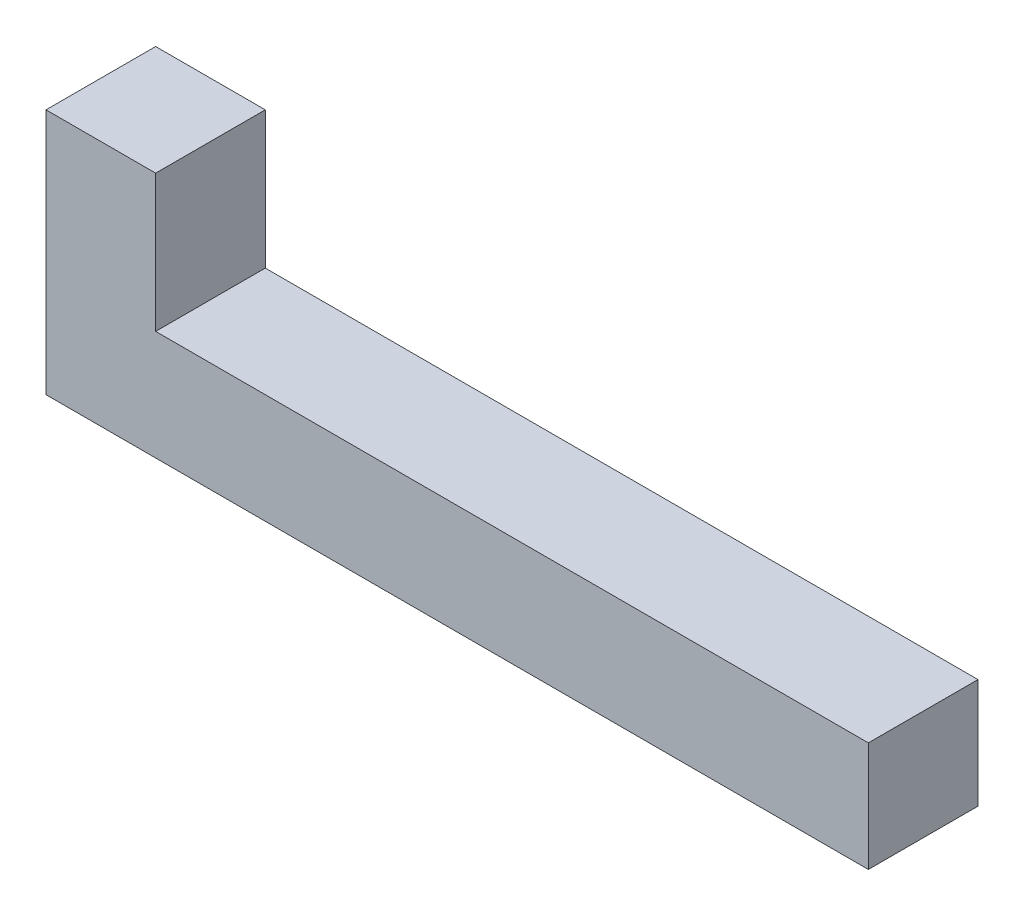
SolidWorks part; units mm, degrees
ref_plane "Front Plane" through (0, 0, 0) normal (0, 0, 1) x (1, 0, 0)
ref_plane "Top Plane" through (0, 0, 0) normal (0, 1, 0) x (1, 0, 0)
ref_plane "Right Plane" through (0, 0, 0) normal (1, 0, 0) x (0, 0, -1)
sketch "Sketch1" plane through (0, 0, 0) normal (0, 0, 1) x (1, 0, 0)
  line L1 (0, 0) -> (200, 0)
  line L2 (0, 0) -> (0, -450)
  line L3 (0, -450) -> (264.0622, -450)
  line L4 (200, 0) -> (200, -250)
  line L5 (264.0622, -450) -> (1500, -450)
  line L7 (200, -250) -> (1500, -250)
  line L8 (1500, -450) -> (1500, -250)
  dimension "D1" = 450
  dimension "D2" = 200
  dimension "D3" = 1300
  dimension "D4" = 250
extrude "Boss-Extrude1" add sketch "Sketch1" along normal blind 200
